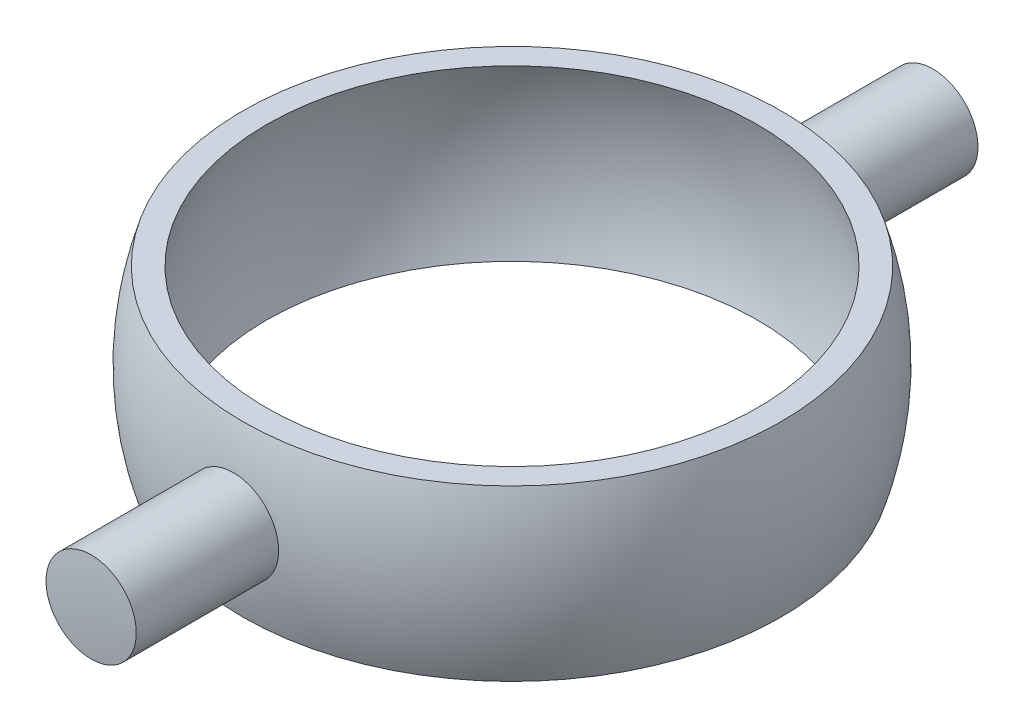
SolidWorks part; units mm, degrees
ref_plane "Front Plane" through (0, 0, 0) normal (0, 0, 1) x (1, 0, 0)
ref_plane "Top Plane" through (0, 0, 0) normal (0, 1, 0) x (1, 0, 0)
ref_plane "Right Plane" through (0, 0, 0) normal (1, 0, 0) x (0, 0, -1)
sketch "Sketch1" plane through (0, 0, 0) normal (0, 0, 1) x (1, 0, 0)
  line L0 (0, 8.8561) -> (0, 0) construction
  line L1 (0, 0) -> (-26.6499, 0) construction
  line L2 (-23.8485, 7.5) -> (-21.7428, 7.5)
  line L3 (-23.8485, -7.5) -> (-21.7428, -7.5)
  arc A0 (-23.8485, 7.5) -> (-23.8485, -7.5) centre (0, 0) ccw
  arc A1 (-21.7428, 7.5) -> (-21.7428, -7.5) centre (0, 0) ccw
  dimension "D1" = 25
  dimension "D2" = 23
  dimension "D3" = 15
revolve "Revolve1" add sketch "Sketch1" angle 360 about L0
ref_plane "Plane1" through (0, 0, 37.5) normal (0, 0, 1) x (1, 0, 0)
sketch "Sketch3" plane through (0, 0, 37.5) normal (0, 0, 1) x (1, 0, 0)
  circle A0 centre (0, 0) radius 4
  dimension "D1" = 8
extrude "Boss-Extrude1" add sketch "Sketch3" against normal up to surface (12.8221 mm away)
mirror "Mirror1" about plane through (0, 0, 0) normal (0, 0, 1) of "Boss-Extrude1"
sketch "Sketch4" plane through (0, 0, 0) normal (1, 0, 0) x (0, 0, -1)
  line L0 (0, 24.2548) -> (0, 0) construction
  line L1 (0, 0) -> (-37.5, 0) construction
  line L2 (-37.5, 4) -> (-37.5, -4) construction
  line L3 (0, 40) -> (0, 37.5)
  line L4 (0, -37.5) -> (0, -40)
  arc A0 (0, 40) -> (0, -40) centre (0, 0) ccw
  arc A1 (0, 37.5) -> (0, -37.5) centre (0, 0) ccw
  dimension "D1" = 40
  dimension "D2" = 37.5
revolve "Cut-Revolve1" cut sketch "Sketch4" angle 360 about L4
